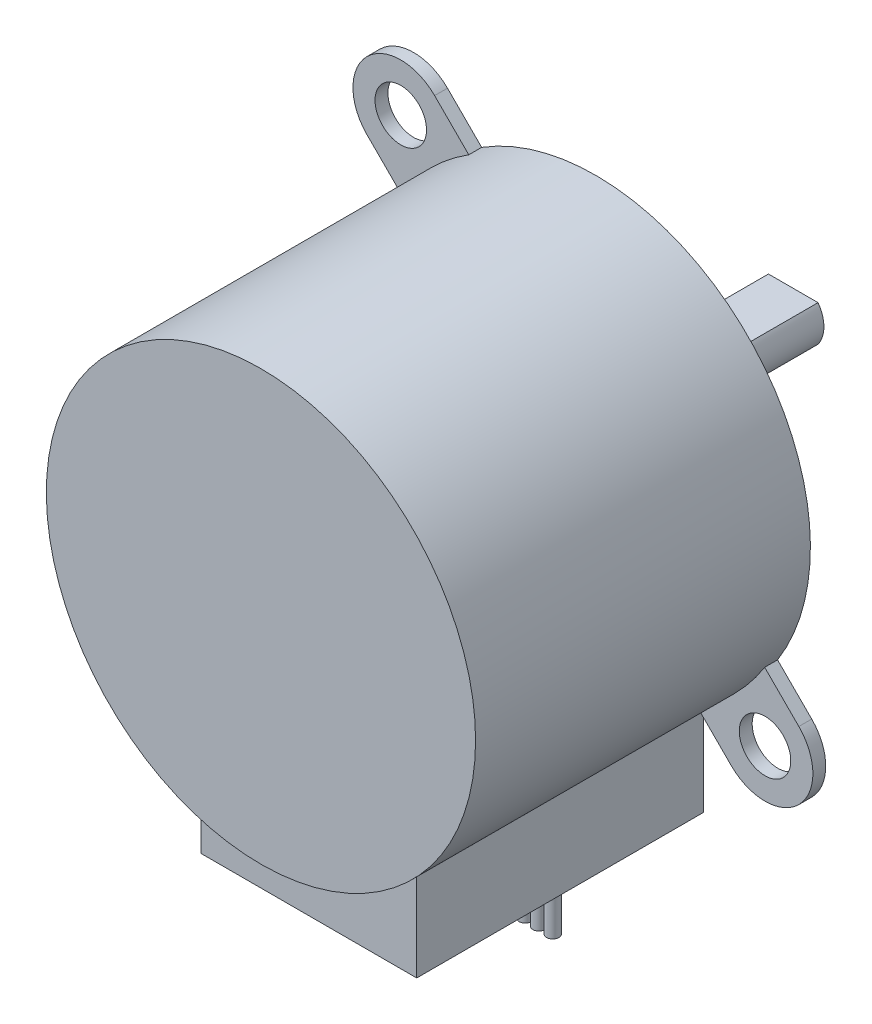
SolidWorks part; units mm, degrees
ref_plane "前视基准面" through (0, 0, 0) normal (0, 0, 1) x (1, 0, 0)
ref_plane "上视基准面" through (0, 0, 0) normal (0, 1, 0) x (1, 0, 0)
ref_plane "右视基准面" through (0, 0, 0) normal (1, 0, 0) x (0, 0, -1)
sketch "草图1" plane through (0, 0, 0) normal (0, 0, 1) x (1, 0, 0)
  circle A0 centre (0, 0) radius 17.5
  dimension "D1" = 35
extrude "凸台-拉伸1" add sketch "草图1" along normal blind 27.3
sketch "草图2" plane through (0, 0, 0) normal (0, 0, -1) x (-1, 0, 0)
  circle A0 centre (0, 0) radius 4.85
  dimension "D1" = 9.7
extrude "凸台-拉伸2" add sketch "草图2" along normal blind 2.5
sketch "草图3" plane through (0, 0, -2.5) normal (0, 0, -1) x (-1, 0, 0)
  circle A0 centre (0, 0) radius 2.5
  dimension "D1" = 5
extrude "凸台-拉伸3" add sketch "草图3" along normal blind 4.6
sketch "草图4" plane through (0, 0, -7.1) normal (0, 0, -1) x (-1, 0, 0)
  line L1 (-6.7109, 1.47) -> (6.7109, 1.47)
  line L2 (-6.7109, 1.47) -> (-6.7109, -1.47)
  line L3 (-6.7109, -1.47) -> (6.7109, -1.47)
  line L4 (6.7109, 1.47) -> (6.7109, -1.47)
  line L5 (-6.7109, 1.47) -> (6.7109, -1.47) construction
  line L6 (-6.7109, -1.47) -> (6.7109, 1.47) construction
  circle A1 centre (0, 0) radius 2.5
  circle A2 centre (0, 0) radius 2.5
  circle M2 centre (0, 0) radius 2.5
  dimension "D2" = 2.94
  dimension "D1" = 0
extrude "凸台-拉伸4" add sketch "草图4" along normal blind 9 contours L3 L1 M2
sketch "草图5" plane through (0, 0, 0) normal (0, 0, -1) x (-1, 0, 0)
  line L1 (-8.8, 23.08) -> (8.8, 23.08)
  line L2 (-8.8, 23.08) -> (-8.8, -23.08)
  line L3 (-8.8, -23.08) -> (8.8, -23.08)
  line L4 (8.8, 23.08) -> (8.8, -23.08)
  line L5 (-8.8, 23.08) -> (8.8, -23.08) construction
  line L6 (-8.8, -23.08) -> (8.8, 23.08) construction
  circle A0 centre (0, 0) radius 17.5 construction
  circle A1 centre (0, 0) radius 17.5
  point P0 (0, 0)
  circle M4 centre (0, 0) radius 17.5
  dimension "D1" = 17.6
  dimension "D2" = 23.08
extrude "凸台-拉伸5" add sketch "草图5" against normal blind 23.4 contours L4 L2 L3 M4
sketch "草图6" plane through (0, 0, 0) normal (0, 0, -1) x (-1, 0, 0)
  line L0 (0, 0) -> (14.8492, 14.8492) construction
  line L1 (9.3055, 14.8209) -> (12.0915, 17.607)
  line L2 (0, 0) -> (-20.2052, 20.2052) construction
  line L3 (0, 0) -> (14.5641, 0) construction
  line L4 (17.607, 12.0915) -> (14.8209, 9.3055)
  line L5 (-12.0915, -17.607) -> (-9.3055, -14.8209)
  line L6 (-14.8209, -9.3055) -> (-17.607, -12.0915)
  circle A0 centre (14.8492, 14.8492) radius 3.9
  arc A1 (8.8, -15.1265) -> (-8.8, -15.1265) centre (0, 0) ccw construction
  arc A2 (8.8, -15.1265) -> (-8.8, -15.1265) centre (0, 0) ccw
  circle A3 centre (-14.8492, -14.8492) radius 3.9
  circle A4 centre (14.8492, 14.8492) radius 2.1
  circle A5 centre (-14.8492, -14.8492) radius 2.1
  arc M8 (8.8, -15.1265) -> (-8.8, -15.1265) centre (0, 0) ccw
  dimension "D3" = 7.8
  dimension "D4" = 4.2
  dimension "D5" = 4.2
  dimension "D1" = 21
  dimension "D2" = 45
extrude "凸台-拉伸6" add sketch "草图6" against normal blind 1.05 contours A3 A2 A5 | A3 L5 M8 | L6 A3 M8 | A0 A4 M8 | A0 L4 M8 | A0 L1 M8
sketch "草图7" plane through (0, -23.08, 0) normal (0, -1, 0) x (1, 0, 0)
  line L0 (0, 0) -> (0, 31.5632) construction
  line L1 (8.8, 0) -> (-8.8, 0) construction
  line L2 (-2, 5.8) -> (2, 5.8) construction
  line L3 (-2, 6.6) -> (2, 6.6)
  line L4 (-2, 5) -> (2, 5)
  arc A0 (-2, 6.6) -> (-2, 5) centre (-2, 5.8) ccw
  arc A1 (2, 5) -> (2, 6.6) centre (2, 5.8) ccw
  point P6 (0, 5.8)
  dimension "D1" = 0.8
  dimension "D2" = 5
  dimension "D3" = 4
extrude "切除-拉伸1" cut sketch "草图7" against normal blind 1.05
sketch "草图8" plane through (0, -22.03, 0) normal (0, -1, 0) x (1, 0, 0)
  line L0 (2.8, 5.8) -> (-2.8, 5.8) construction
  arc A0 (2, 5) -> (2, 6.6) centre (2, 5.8) ccw construction
  arc A1 (-2, 6.6) -> (-2, 5) centre (-2, 5.8) ccw construction
  circle A2 centre (2.288, 5.8) radius 0.5
  circle A3 centre (1.168, 5.8) radius 0.5
  circle A4 centre (0.048, 5.8) radius 0.5
  circle A5 centre (-1.072, 5.8) radius 0.5
  circle A6 centre (-2.192, 5.8) radius 0.5
  dimension "D1" = 1
  dimension "D2" = 5
extrude "凸台-拉伸7" add sketch "草图8" along normal blind 10
